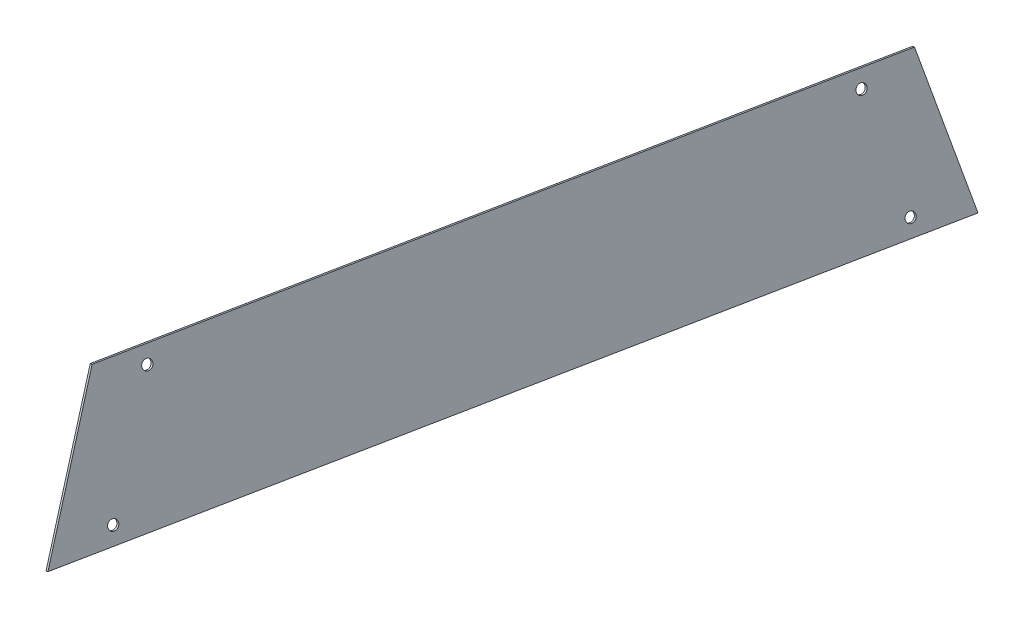
SolidWorks part; units mm, degrees
material "Thornel VCB-20 Carbon Cloth"
ref_plane "Front Plane" through (0, 0, 0) normal (0, 0, 1) x (1, 0, 0)
ref_plane "Top Plane" through (0, 0, 0) normal (0, 1, 0) x (1, 0, 0)
ref_plane "Right Plane" through (0, 0, 0) normal (1, 0, 0) x (0, 0, -1)
ref_plane "Plane1" through (661.4861, 211.2284, 131.5661) normal (0.936, 0.2989, 0.1862) x (0.1773, 0.0566, -0.9825)
sketch "Sketch1" plane through (661.4861, 211.2284, 131.5661) normal (0.936, 0.2989, 0.1862) x (0.1773, 0.0566, -0.9825)
  line L0 (-1754.3799, 458.8009) -> (-1797.0991, 381.1991)
  line L1 (-1797.0991, 381.1991) -> (-1334.0947, 353.676)
  line L2 (-1334.0947, 353.676) -> (-1345.0129, 434.4662)
  line L3 (-1345.0129, 434.4662) -> (-1754.3799, 458.8009)
  line L4 (-1428.3419, 1051.0671) -> (-1868.8378, 250.8817) construction
  line L5 (-1428.3419, 1051.0671) -> (-1321.2913, 258.9362) construction
  line L7 (-1743.5355, 443.0568) -> (-1770.1572, 394.697) construction
  line L8 (-1762.4286, 444.1799) -> (-1724.6424, 441.9337) construction
  line L9 (-1756.8464, 418.8769) -> (-1775.7395, 420) construction
  line L10 (-1544.2893, 840.4421) -> (-1398.708, 831.7881) construction
  line L12 (-1756.8982, 393.9089) -> (-1789.0503, 395.8201) construction
  point P8 (-1775.7395, 420)
  point P10 (-1756.8464, 418.8769)
  point P14 (-1749.3926, 467.8606)
  point P15 (-1822.8616, 334.4001)
  point P16 (-1736.6371, 491.0317)
  point P17 (0, 0)
  point P18 (0, 0)
  point P24 (-1805.7874, 365.4162)
  point P26 (0, 0)
  dimension "D1" = 80
extrude "Boss-Extrude1" add sketch "Sketch1" along normal blind 1.5
sketch "Sketch3" plane through (661.4861, 211.2284, 131.5661) normal (0.936, 0.2989, 0.1862) x (0.1773, 0.0566, -0.9825)
  line L0 (-1373.0164, 365.0786) -> (-1357.5437, 364.1588) construction
  line L1 (-1365.9854, 426.624) -> (-1381.4581, 427.5438) construction
  line L2 (-1737.0139, 448.6797) -> (-1721.5412, 447.7599) construction
  line L3 (-1769.9818, 388.676) -> (-1754.5091, 387.7563) construction
  circle A0 centre (-1729.2776, 448.2198) radius 2.75
  circle A1 centre (-1762.2454, 388.2161) radius 2.75
  circle A2 centre (-1365.2801, 364.6187) radius 2.75
  circle A3 centre (-1373.7218, 427.0839) radius 2.75
  arc A4 (-1370.1081, 367.6605) -> (-1370.4344, 362.1702) centre (-1370.2712, 364.9154) ccw construction
  arc A5 (-1360.4521, 361.5768) -> (-1360.1257, 367.0671) centre (-1360.2889, 364.322) ccw construction
  arc A6 (-1368.8938, 424.0421) -> (-1368.5674, 429.5324) centre (-1368.7306, 426.7872) ccw construction
  arc A7 (-1378.5498, 430.1258) -> (-1378.8761, 424.6355) centre (-1378.713, 427.3806) ccw construction
  arc A8 (-1734.1056, 451.2617) -> (-1734.4319, 445.7713) centre (-1734.2688, 448.5165) ccw construction
  arc A9 (-1724.4496, 445.178) -> (-1724.1232, 450.6683) centre (-1724.2864, 447.9231) ccw construction
  arc A10 (-1767.0734, 391.258) -> (-1767.3998, 385.7677) centre (-1767.2366, 388.5128) ccw construction
  arc A11 (-1757.4174, 385.1743) -> (-1757.0911, 390.6646) centre (-1757.2542, 387.9194) ccw construction
  point P16 (-1760.3362, 388.1026)
  dimension "D1" = 5.5
  dimension "D2" = 5.5
  dimension "D3" = 5.5
  dimension "D4" = 5.5
extrude "Cut-Extrude1" cut sketch "Sketch3" against normal through all both and the other way through all
